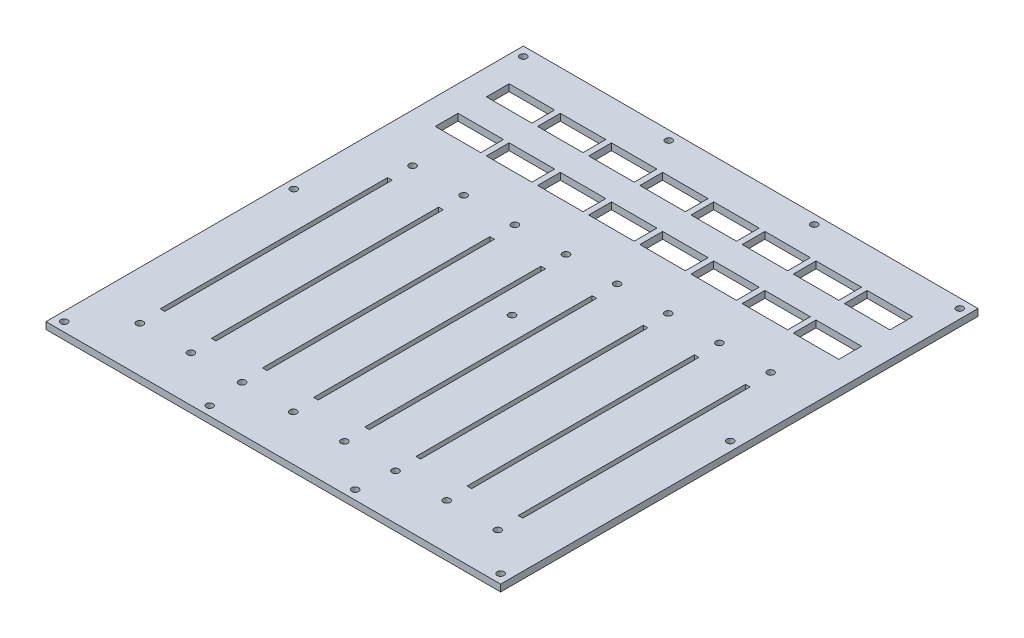
SolidWorks part; units mm, degrees
ref_plane "Front Plane" through (0, 0, 0) normal (0, 0, 1) x (1, 0, 0)
ref_plane "Top Plane" through (0, 0, 0) normal (0, 1, 0) x (1, 0, 0)
ref_plane "Right Plane" through (0, 0, 0) normal (1, 0, 0) x (0, 0, -1)
sketch "Sketch1" plane through (0, 0, 0) normal (0, 1, 0) x (1, 0, 0)
  line L1 (100, 105) -> (-100, 105)
  line L2 (100, 105) -> (100, -105)
  line L3 (100, -105) -> (-100, -105)
  line L4 (-100, 105) -> (-100, -105)
  line L5 (100, 105) -> (-100, -105) construction
  line L6 (100, -105) -> (-100, 105) construction
  point P0 (0, 0)
  dimension "D1" = 200
  dimension "D2" = 210
extrude "Boss-Extrude1" add sketch "Sketch1" along normal blind 3
sketch "Sketch2" plane through (0, 3, 0) normal (0, 1, 0) x (1, 0, 0)
  line L0 (-79.75, 25) -> (-77.75, 25)
  line L1 (-79.75, 25) -> (-79.75, -75)
  line L2 (-79.75, -75) -> (-77.75, -75)
  line L3 (-77.75, 25) -> (-77.75, -75)
  line L4 (-79.75, 25) -> (-77.75, -75) construction
  line L5 (-79.75, -75) -> (-77.75, 25) construction
  line L6 (-100, 105) -> (-100, -105) construction
  circle A0 centre (-78.75, -85) radius 1.5
  circle A1 centre (-78.75, 35) radius 1.5
  point P0 (-78.75, -25)
  dimension "D3" = 3
  dimension "D4" = 3
  dimension "D1" = 100
  dimension "D2" = 2
  dimension "D5" = 120
  dimension "D6" = 60
  dimension "D7" = 78.75
  dimension "D8" = 25
extrude "Cut-Extrude1" cut sketch "Sketch2" against normal up to next
pattern_linear "LPattern1" count 8 spacing 22.5 along (1, 0, 0) of "Cut-Extrude1"
sketch "Sketch3" plane through (0, 3, 0) normal (0, 1, 0) x (1, 0, 0)
  line L1 (-88.75, 55) -> (-68.75, 55)
  line L2 (-88.75, 55) -> (-88.75, 65)
  line L3 (-88.75, 65) -> (-68.75, 65)
  line L4 (-68.75, 55) -> (-68.75, 65)
  line L5 (-88.75, 55) -> (-68.75, 65) construction
  line L6 (-88.75, 65) -> (-68.75, 55) construction
  circle A0 centre (-78.75, 35) radius 1.5 construction
  point P0 (-78.75, 60)
  dimension "D1" = 20
  dimension "D2" = 10
  dimension "D3" = 1
  dimension "D4" = 25
extrude "Cut-Extrude2" cut sketch "Sketch3" against normal up to next
pattern_linear "LPattern2" count 8 spacing 22.5 along (1, 0, 0) count 2 spacing 22.5 along (0, 0, -1) of "Cut-Extrude2"
sketch "Sketch4" plane through (0, 3, 0) normal (0, 1, 0) x (1, 0, 0)
  line L0 (100, 105) -> (-100, 105) construction
  line L1 (-100, 105) -> (-100, -105) construction
  circle A1 centre (-96, 101) radius 1.5
  dimension "D2" = 3
  dimension "D3" = 4
  dimension "D4" = 4
extrude "Cut-Extrude3" cut sketch "Sketch4" against normal up to next
pattern_linear "LPattern3" count 4 spacing 64 along (1, 0, 0) of "Cut-Extrude3"
pattern_linear "LPattern4" count 2 spacing 202 along (0, 0, 1) of "LPattern3", "Cut-Extrude3"
sketch "Sketch8" plane through (0, 3, 0) normal (0, 1, 0) x (1, 0, 0)
  circle A0 centre (0, 0) radius 1.5
  dimension "D1" = 3
extrude "Cut-Extrude4" cut sketch "Sketch8" against normal up to next
sketch "Sketch9" plane through (0, 3, 0) normal (0, 1, 0) x (1, 0, 0)
  line L0 (-100, 105) -> (-100, -105) construction
  line L1 (100, -105) -> (100, 105) construction
  circle A0 centre (-96, 0) radius 1.5
  circle A1 centre (96, 0) radius 1.5
  dimension "D1" = 3
  dimension "D3" = 3
  dimension "D2" = 4
  dimension "D4" = 4
extrude "Cut-Extrude5" cut sketch "Sketch9" against normal up to next
